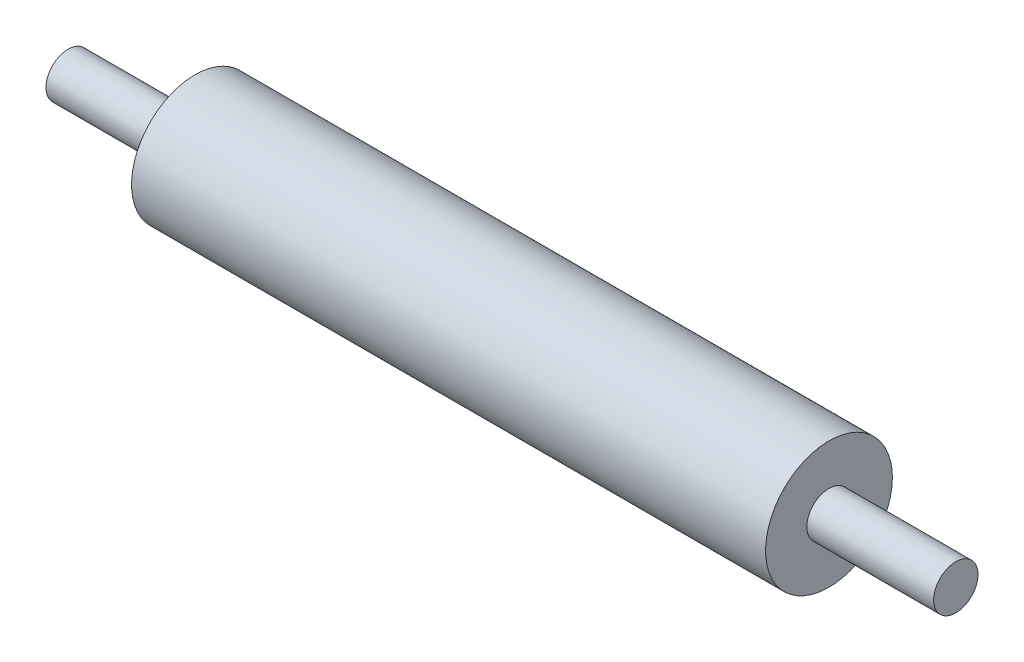
SolidWorks part; units mm, degrees
ref_plane "Front Plane" through (0, 0, 0) normal (0, 0, 1) x (1, 0, 0)
ref_plane "Top Plane" through (0, 0, 0) normal (0, 1, 0) x (1, 0, 0)
ref_plane "Right Plane" through (0, 0, 0) normal (1, 0, 0) x (0, 0, -1)
sketch "Sketch1" plane through (0, 0, 0) normal (1, 0, 0) x (0, 0, -1)
  circle A0 centre (0, 0) radius 10
  dimension "D1" = 20
extrude "Boss-Extrude1" add sketch "Sketch1" along normal mid plane 100
sketch "Sketch2" plane through (50, 0, 0) normal (1, 0, 0) x (0, 0, -1)
  circle A0 centre (0, 0) radius 3.5
  dimension "D1" = 7
extrude "Boss-Extrude2" add sketch "Sketch2" along normal blind 20
mirror "Mirror1" about plane through (0, 0, 0) normal (1, 0, 0) of "Boss-Extrude2"
